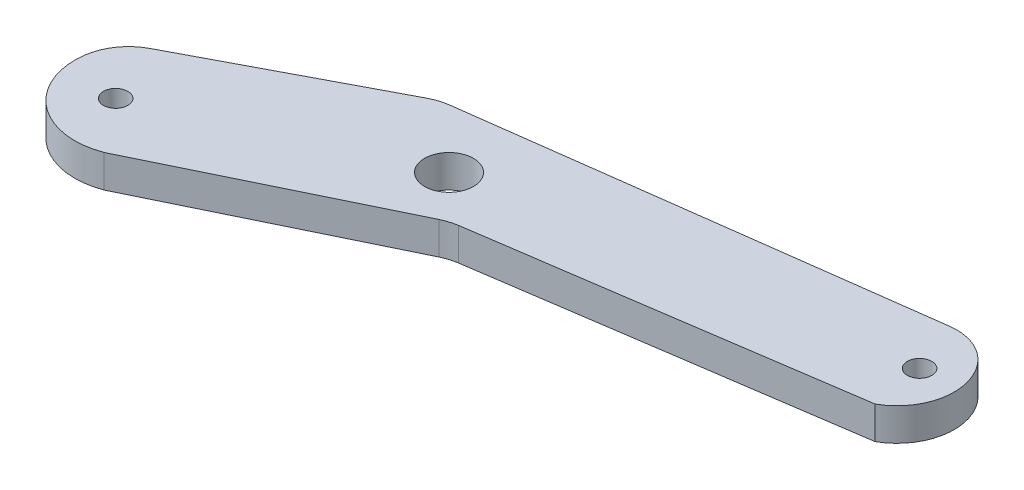
SolidWorks part; units mm, degrees
ref_plane "Alzado" through (0, 0, 0) normal (0, 0, 1) x (1, 0, 0)
ref_plane "Planta" through (0, 0, 0) normal (0, 1, 0) x (1, 0, 0)
ref_plane "Vista lateral" through (0, 0, 0) normal (1, 0, 0) x (0, 0, -1)
sketch "Croquis1" plane through (0, 0, 0) normal (0, 1, 0) x (1, 0, 0)
  line L3 (47.875, 0) -> (47.875, 60.1302) construction
  line L5 (103.9559, 6.2004) -> (100.5984, 26.9302) construction
  line L6 (103.9559, 6.2004) -> (33.1827, -4.2505)
  line L7 (-12.7, -4.7625) -> (-12.7, 38.5825) construction
  line L10 (-21.6937, -80.0806) -> (-21.6937, 3.7748) construction
  line L11 (-13.7071, -26.4826) -> (-29.6803, -5.9678) construction
  line L12 (8.6116, 14.1472) -> (-26.7513, -4.4292)
  line L13 (30.2792, -5.1459) -> (-13.7071, -26.4826)
  line L14 (11.9511, 15.208) -> (98.0899, 26.5985)
  circle A0 centre (102.2772, 16.5653) radius 2.3813
  circle A1 centre (23.3063, 3.7748) radius 4.7625
  arc A2 (107.2405, 22.8928) -> (103.9559, 6.2004) centre (98.4715, 15.9489) cw
  circle A3 centre (-21.6937, -16.2252) radius 2.3812
  arc A4 (-32.0126, -11.9568) -> (-13.7071, -26.4826) centre (-18.5273, -13.7598) ccw
  arc A5 (11.9511, 15.208) -> (8.6116, 14.1472) centre (13.2621, 5.2943) ccw
  arc A6 (33.1827, -4.2505) -> (30.2792, -5.1459) centre (34.6436, -14.1432) ccw
  arc A7 (-32.0126, -11.9568) -> (-26.7513, -4.4292) centre (-22.1008, -13.282) cw
  arc A8 (98.0899, 26.5985) -> (107.2405, 22.8928) centre (99.4008, 16.6848) cw
  point P3 (0, 0)
  point P13 (102.2772, 16.5653)
  point P16 (23.3063, -0.9877)
  point P20 (102.2772, 16.5653)
  point P29 (-21.6937, -16.2252)
  dimension "D4" = 4.7625
  dimension "D5" = 9.525
  dimension "D13" = 4.7625
  dimension "D10" = 10
  dimension "D16" = 10
  dimension "D17" = 10
  dimension "D2" = 11.0695
  dimension "D3" = 80
  dimension "D6" = 45
  dimension "D8" = 21
  dimension "D14" = 26
extrude "Saliente-Extruir1" add sketch "Croquis1" along normal blind 6.35
sketch "Croquis2" plane through (0, 6.35, 0) normal (0, 1, 0) x (1, 0, 0)
  line L0 (102.2772, 16.5653) -> (117.8491, 16.5653) construction
  line L1 (99.4008, 26.6848) -> (119.4821, 26.6848) construction
  arc A1 (107.2405, 22.8928) -> (98.0899, 26.5985) centre (99.4008, 16.6848) ccw construction
  point P0 (102.2772, 16.5653)
  dimension "D1" = 10.1195
